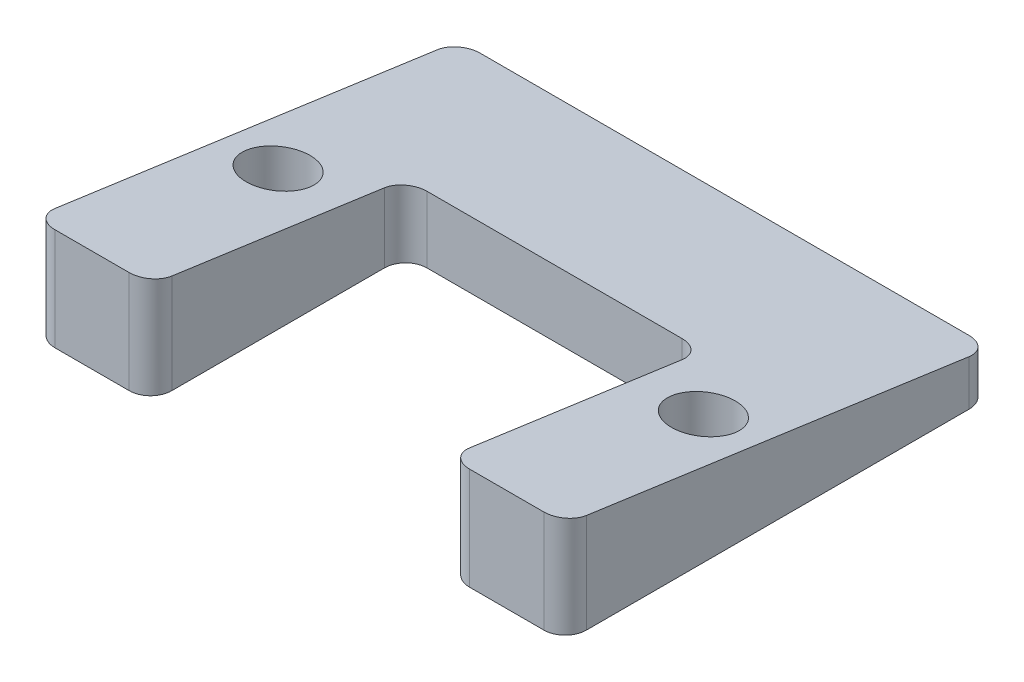
SolidWorks part; units mm, degrees
ref_plane "Plan de face" through (0, 0, 0) normal (0, 0, 1) x (1, 0, 0)
ref_plane "Plan de dessus" through (0, 0, 0) normal (0, 1, 0) x (1, 0, 0)
ref_plane "Plan de droite" through (0, 0, 0) normal (1, 0, 0) x (0, 0, -1)
sketch "Esquisse1" plane through (0, 0, 0) normal (0, 1, 0) x (1, 0, 0)
  line L1 (7, -9) -> (12.5, -9)
  line L2 (7, -9) -> (7, 3)
  line L4 (12.5, -9) -> (12.5, 11)
  line L5 (12.5, 11) -> (0, 11)
  line L7 (7, 3) -> (0, 3)
  line L8 (0, 11) -> (0, 3)
  circle A0 centre (10, 0) radius 1.5
  dimension "D1" = 10
  dimension "D2" = 3
  dimension "D4" = 9
  dimension "D3" = 12.5
  dimension "D5" = 7
  dimension "D6" = 3
  dimension "D7" = 11
extrude "Boss.-Extru.1" add sketch "Esquisse1" along normal blind 10
sketch "Esquisse2" plane through (12.5, 0, 0) normal (1, 0, 0) x (0, 0, -1)
  line L0 (11, 10) -> (11, 0) construction
  line L1 (-9, 10) -> (11, 10)
  line L2 (-9, 10) -> (-9, 4.8108)
  line L3 (-9, 4.8108) -> (11, 2)
  line L4 (11, 10) -> (11, 2)
  line L5 (-9, 0) -> (11, 0) construction
  dimension "D1" = 2
  dimension "D2" = 8
extrude "Enlèv. mat.-Extru.1" cut sketch "Esquisse2" against normal through all
fillet "Congé1" radius 1 4 edges at (12.5, 1, -11) (12.5, 2.4054, 9) (7, 2.4054, 9) (7, 1.5622, -3)
mirror "Symétrie1" about plane through (0, 10, -11) normal (1, 0, 0) of bodies 102
ref_point "Point1"
ref_point "Point2"
